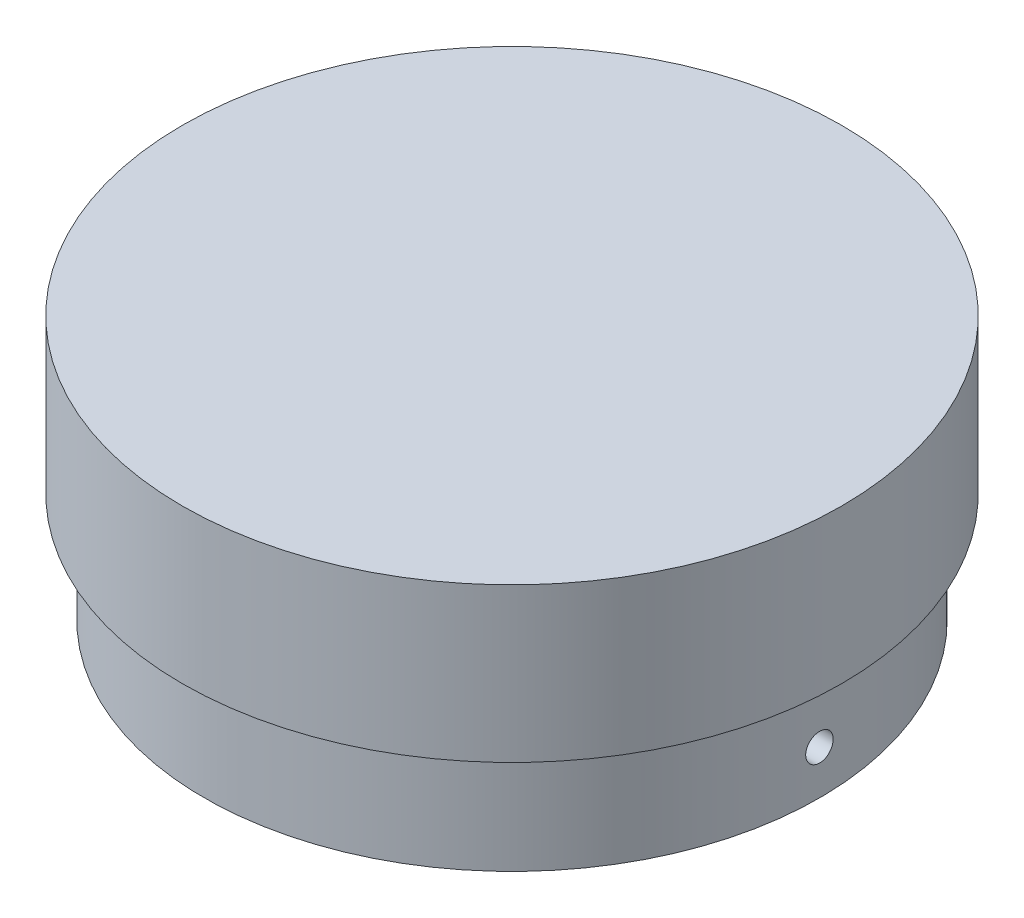
SolidWorks part; units mm, degrees
material "Polyethylene Cross-Linked"
ref_plane "Front Plane" through (0, 0, 0) normal (0, 0, 1) x (1, 0, 0)
ref_plane "Top Plane" through (0, 0, 0) normal (0, 1, 0) x (1, 0, 0)
ref_plane "Right Plane" through (0, 0, 0) normal (1, 0, 0) x (0, 0, -1)
sketch "Sketch1" plane through (0, 0, 0) normal (0, 0, 1) x (1, 0, 0)
  line L0 (0, 0) -> (0, 92.3285) construction
  line L1 (0, 0) -> (88.9, 0)
  line L2 (88.9, 0) -> (88.9, 31.75)
  line L3 (88.9, 31.75) -> (95.25, 31.75)
  line L4 (95.25, 31.75) -> (95.25, 76.2)
  line L5 (95.25, 76.2) -> (0, 76.2)
  line L6 (0, 76.2) -> (0, 0)
  dimension "D1" = 95.25
  dimension "D2" = 6.35
  dimension "D3" = 31.75
  dimension "D4" = 44.45
revolve "Revolve1" add sketch "Sketch1" angle 360 about L0
ref_plane "Plane1" through (0, 0, 101) normal (0, 0, 1) x (1, 0, 0)
ref_plane "Plane2" through (88.9, 0, 0) normal (1, 0, 0) x (0, 0, -1)
sketch "Sketch3" plane through (88.9, 0, 0) normal (1, 0, 0) x (0, 0, -1)
  line L0 (-88.9, 0) -> (88.9, 0) construction
  circle A0 centre (0, 12.7) radius 3.9688
  dimension "D1" = 7.9375
  dimension "D2" = 12.7
extrude "Cut-Extrude1" cut sketch "Sketch3" against normal blind 12.7 contours A0
pattern_circular "CirPattern2" count 2 every 180 about axis through (0, 0, 0) along (0, -1, 0) of "Cut-Extrude1"
